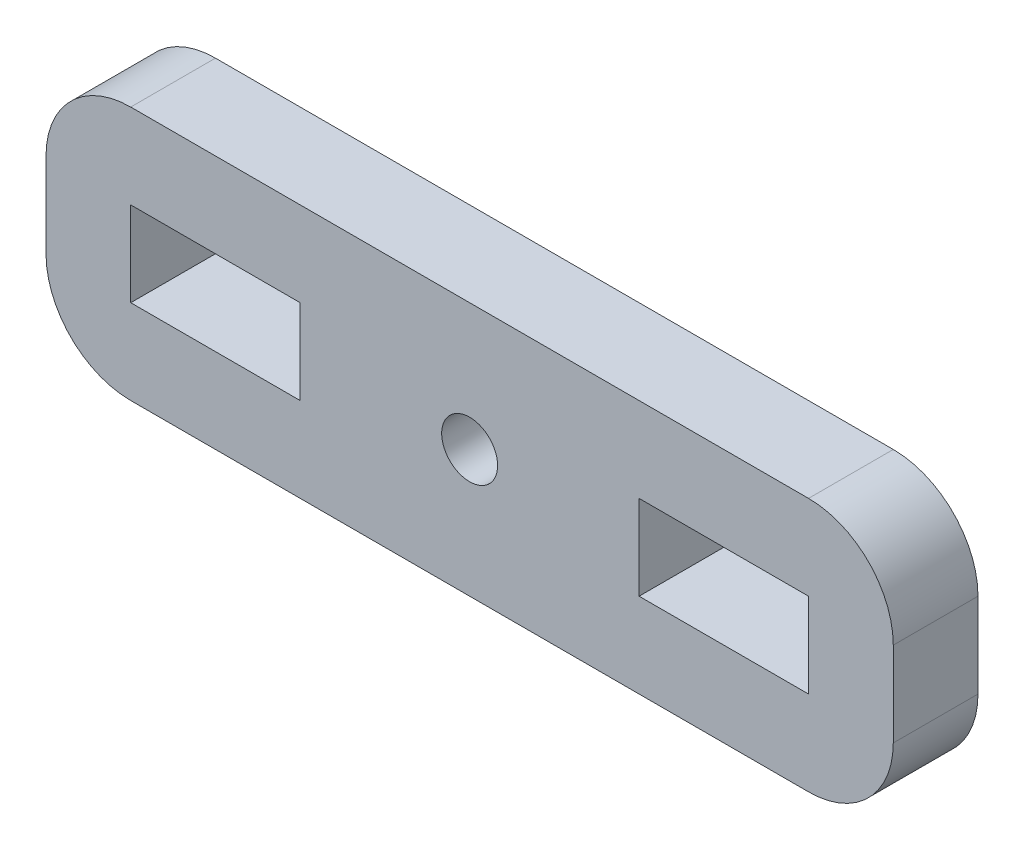
SolidWorks part; units mm, degrees
ref_plane "Front Plane" through (0, 0, 0) normal (0, 0, 1) x (1, 0, 0)
ref_plane "Top Plane" through (0, 0, 0) normal (0, 1, 0) x (1, 0, 0)
ref_plane "Right Plane" through (0, 0, 0) normal (1, 0, 0) x (0, 0, -1)
sketch "Sketch1" plane through (0, 0, 0) normal (0, 0, 1) x (1, 0, 0)
  line L1 (-31.75, -9.525) -> (31.75, -9.525)
  line L2 (-31.75, -9.525) -> (-31.75, 9.525)
  line L3 (-31.75, 9.525) -> (31.75, 9.525)
  line L4 (31.75, -9.525) -> (31.75, 9.525)
  line L5 (-31.75, -9.525) -> (31.75, 9.525) construction
  line L6 (-31.75, 9.525) -> (31.75, -9.525) construction
  point P0 (0, 0)
  dimension "D1" = 19.05
  dimension "D2" = 63.5
extrude "Boss-Extrude1" add sketch "Sketch1" along normal blind 6.35
sketch "Sketch2" plane through (0, 0, 6.35) normal (0, 0, 1) x (1, 0, 0)
  line L0 (0, 3.175) -> (0, -3.175) construction
  line L1 (-31.75, -9.525) -> (31.75, -9.525) construction
  line L2 (-31.75, -3.175) -> (31.75, -3.175) construction
  line L3 (-31.75, 9.525) -> (-31.75, -9.525) construction
  line L4 (31.75, -9.525) -> (31.75, 9.525) construction
  line L5 (-31.75, 3.175) -> (31.75, 3.175) construction
  line L7 (-25.4, 3.175) -> (-12.7, 3.175)
  line L8 (-25.4, 3.175) -> (-25.4, -3.175)
  line L9 (-25.4, -3.175) -> (-12.7, -3.175)
  line L10 (-12.7, 3.175) -> (-12.7, -3.175)
  line L11 (12.7, 3.175) -> (25.4, 3.175)
  line L12 (12.7, 3.175) -> (12.7, -3.175)
  line L13 (12.7, -3.175) -> (25.4, -3.175)
  line L14 (25.4, 3.175) -> (25.4, -3.175)
  circle A0 centre (0, 0) radius 2.0955
  dimension "D3" = 4.191
  dimension "D1" = 6.35
  dimension "D2" = 6.35
  dimension "D4" = 12.7
  dimension "D5" = 12.7
  dimension "D6" = 12.7
  dimension "D7" = 12.7
extrude "Cut-Extrude1" cut sketch "Sketch2" against normal blind 6.35
fillet "Fillet1" radius 6.35 4 edges at (-31.75, -9.525, 3.175) (31.75, -9.525, 3.175) (31.75, 9.525, 3.175) (-31.75, 9.525, 3.175)
